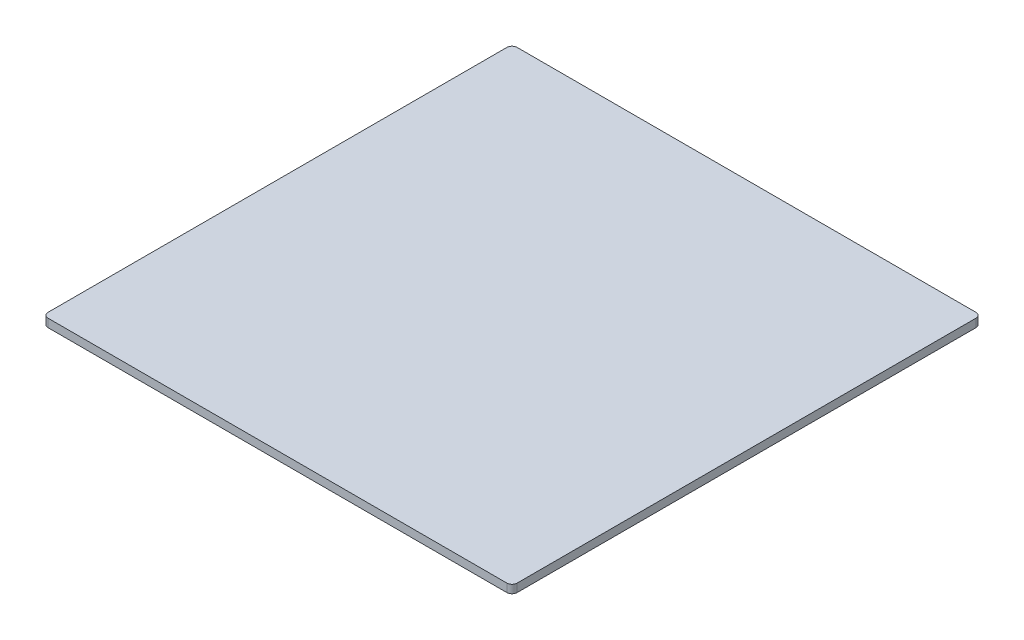
SolidWorks part; units mm, degrees
ref_plane "Front Plane" through (0, 0, 0) normal (0, 0, 1) x (1, 0, 0)
ref_plane "Top Plane" through (0, 0, 0) normal (0, 1, 0) x (1, 0, 0)
ref_plane "Right Plane" through (0, 0, 0) normal (1, 0, 0) x (0, 0, -1)
sketch "Sketch1" plane through (0, 0, 0) normal (0, 1, 0) x (1, 0, 0)
  line L0 (-47.5, -44.5) -> (-47.5, 44.5)
  line L1 (-44.5, -45.5) -> (44.5, -45.5)
  line L2 (-45.5, -44.5) -> (-45.5, 44.5)
  line L3 (-44.5, 45.5) -> (44.5, 45.5)
  line L4 (45.5, -44.5) -> (45.5, 44.5)
  line L5 (-45.5, -45.5) -> (45.5, 45.5) construction
  line L6 (-45.5, 45.5) -> (45.5, -45.5) construction
  line L7 (-44.5, 47.5) -> (44.5, 47.5)
  line L8 (47.5, -44.5) -> (47.5, 44.5)
  line L9 (-44.5, -47.5) -> (44.5, -47.5)
  arc A0 (44.5, -45.5) -> (45.5, -44.5) centre (44.5, -44.5) ccw
  arc A1 (-44.5, -45.5) -> (-45.5, -44.5) centre (-44.5, -44.5) cw
  arc A2 (44.5, 45.5) -> (45.5, 44.5) centre (44.5, 44.5) cw
  arc A3 (-45.5, 44.5) -> (-44.5, 45.5) centre (-44.5, 44.5) cw
  arc A4 (-47.5, 44.5) -> (-44.5, 47.5) centre (-44.5, 44.5) cw
  arc A5 (44.5, 47.5) -> (47.5, 44.5) centre (44.5, 44.5) cw
  arc A6 (44.5, -47.5) -> (47.5, -44.5) centre (44.5, -44.5) ccw
  arc A7 (-44.5, -47.5) -> (-47.5, -44.5) centre (-44.5, -44.5) cw
  point P0 (0, 0)
  dimension "D2" = 1
  dimension "D1" = 91
  dimension "D3" = 2
extrude "Boss-Extrude1" add sketch "Sketch1" against normal blind 1.6 contours A3 L2 A1 L1 A0 L4 A2 L3
sketch "Sketch3" plane through (0, 0, 0) normal (0, 1, 0) x (1, 0, 0)
  line L2 (6.5, 7.5) -> (-6.5, 7.5)
  line L3 (-7.5, 6.5) -> (-7.5, -6.5)
  line L4 (44.5, 45.5) -> (-44.5, 45.5)
  line L5 (-45.5, 44.5) -> (-45.5, -44.5)
  line L6 (-44.5, -45.5) -> (44.5, -45.5)
  line L7 (45.5, -44.5) -> (45.5, 44.5)
  line L8 (44.5, 45.5) -> (-44.5, 45.5)
  line L9 (-45.5, 44.5) -> (-45.5, -44.5)
  line L10 (-44.5, -45.5) -> (44.5, -45.5)
  line L11 (45.5, -44.5) -> (45.5, 44.5)
  line L12 (-6.5, -7.5) -> (6.5, -7.5)
  line L13 (7.5, -6.5) -> (7.5, 6.5)
  line L14 (-6.5, 6.5) -> (6.5, -6.5) construction
  line L15 (6.5, 6.5) -> (-6.5, -6.5) construction
  arc A0 (-6.5, 7.5) -> (-7.5, 6.5) centre (-6.5, 6.5) ccw
  arc A1 (-7.5, -6.5) -> (-6.5, -7.5) centre (-6.5, -6.5) ccw
  arc A2 (6.5, -7.5) -> (7.5, -6.5) centre (6.5, -6.5) ccw
  arc A3 (7.5, 6.5) -> (6.5, 7.5) centre (6.5, 6.5) ccw
  arc A4 (-44.5, 45.5) -> (-45.5, 44.5) centre (-44.5, 44.5) ccw
  arc A5 (-45.5, -44.5) -> (-44.5, -45.5) centre (-44.5, -44.5) ccw
  arc A6 (44.5, -45.5) -> (45.5, -44.5) centre (44.5, -44.5) ccw
  arc A7 (45.5, 44.5) -> (44.5, 45.5) centre (44.5, 44.5) ccw
  arc A8 (-44.5, 45.5) -> (-45.5, 44.5) centre (-44.5, 44.5) ccw
  arc A9 (-45.5, -44.5) -> (-44.5, -45.5) centre (-44.5, -44.5) ccw
  arc A10 (44.5, -45.5) -> (45.5, -44.5) centre (44.5, -44.5) ccw
  arc A11 (45.5, 44.5) -> (44.5, 45.5) centre (44.5, 44.5) ccw
  point P2 (0, 0)
  dimension "D2" = 1
  dimension "D3" = 15
  dimension "D1" = 0
